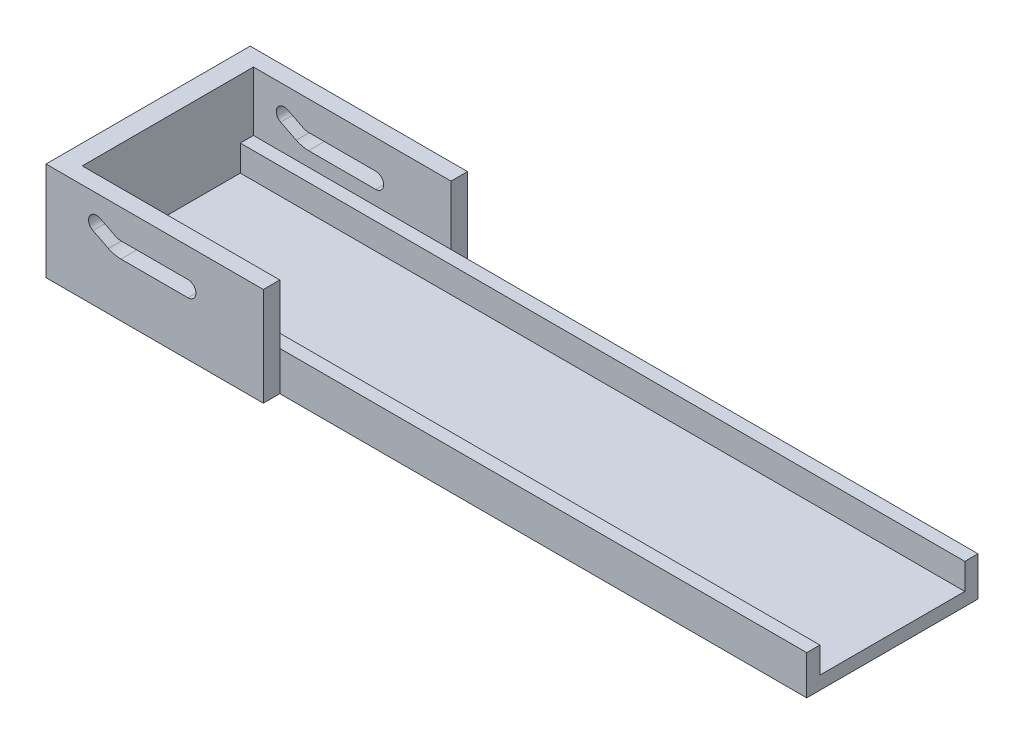
SolidWorks part; units mm, degrees
ref_plane "前视基准面" through (0, 0, 0) normal (0, 0, 1) x (1, 0, 0)
ref_plane "上视基准面" through (0, 0, 0) normal (0, 1, 0) x (1, 0, 0)
ref_plane "右视基准面" through (0, 0, 0) normal (1, 0, 0) x (0, 0, -1)
other "Configuration Table"
sketch "草图1" plane through (0, 0, 0) normal (1, 0, 0) x (0, 0, -1)
  line L0 (-13, 5.95) -> (-13, -5.95)
  line L1 (-11, 3.95) -> (11, 3.95)
  line L2 (-11, 3.95) -> (-11, -3.95)
  line L3 (-11, -3.95) -> (11, -3.95)
  line L4 (11, 3.95) -> (11, -3.95)
  line L5 (-11, 3.95) -> (11, -3.95) construction
  line L6 (-11, -3.95) -> (11, 3.95) construction
  line L7 (-13, -5.95) -> (13, -5.95)
  line L8 (13, 5.95) -> (13, -5.95)
  line L9 (-13, 5.95) -> (13, 5.95)
  line L10 (55, 0) -> (-55, 0) construction
  point P0 (0, 0)
  point P9 (0, 0)
  point P12 (0, 0)
  dimension "D1" = 7.9
  dimension "D2" = 22
  dimension "D3" = 2
extrude "凸台-拉伸1" add sketch "草图1" along normal blind 110
sketch "草图3" plane through (0, 0, 13) normal (0, 0, 1) x (1, 0, 0)
  line L0 (3.6643, 3.3873) -> (3.6643, 5.95)
  line L1 (110, 5.95) -> (0, 5.95) construction
  line L2 (5.6643, 3.3873) -> (5.6643, 5.95)
  line L3 (5.6643, 5.95) -> (3.6643, 5.95)
  line L5 (-3.2135, 0) -> (147.8577, 0)
  line L6 (-3.2135, 0) -> (-3.2135, 8.5216)
  line L7 (-3.2135, 8.5216) -> (147.8577, 8.5216)
  line L8 (147.8577, 0) -> (147.8577, 8.5216)
  arc A0 (3.6643, 3.3873) -> (5.6643, 3.3873) centre (4.6643, 3.3873) ccw
  point P1 (147.8577, 8.5216)
  dimension "D1" = 2
extrude "切除-拉伸1" cut sketch "草图3" against normal blind 50 contours L7 L8 L5 L6
sketch "草图4" plane through (0, 0, 0) normal (-1, 0, 0) x (0, 0, 1)
  line L0 (0, -6.545) -> (0, 6.545) construction
  line L5 (13, 9.0004) -> (15.5, 9.0004)
  line L6 (-13, -5.95) -> (-15.5, -5.95)
  line L7 (15.5, -5.95) -> (15.5, 9.0004)
  line L8 (-13, -5.95) -> (-13, 9.0004)
  line L9 (-13, 9.0004) -> (-15.5, 9.0004)
  line L10 (-15.5, -5.95) -> (-15.5, 9.0004)
  line L11 (13, -5.95) -> (15.5, -5.95)
  line L12 (13, -5.95) -> (13, 9.0004)
  dimension "D1" = 2.5
extrude "凸台-拉伸2" add sketch "草图4" against normal blind 30
sketch "草图5" plane through (0, 0, 0) normal (-1, 0, 0) x (0, 0, 1)
  line L1 (-15.5, 9.0004) -> (15.5, 9.0004)
  line L2 (-15.5, 9.0004) -> (-15.5, -5.95)
  line L3 (-15.5, -5.95) -> (15.5, -5.95)
  line L4 (15.5, 9.0004) -> (15.5, -5.95)
extrude "凸台-拉伸3" add sketch "草图5" along normal blind 3
sketch "草图6" plane through (0, 0, -13) normal (0, 0, 1) x (1, 0, 0)
  line L0 (4.6643, 4.8873) -> (7.6643, 3.3873) construction
  line L1 (5.201, 5.9606) -> (8.201, 4.4606)
  line L2 (4.1276, 3.814) -> (7.1276, 2.314)
  line L3 (7.6643, 3.3873) -> (18.5632, 3.3873) construction
  line L4 (7.6643, 4.5873) -> (18.5632, 4.5873)
  line L5 (7.6643, 2.1873) -> (18.5632, 2.1873)
  arc A0 (5.201, 5.9606) -> (4.1276, 3.814) centre (4.6643, 4.8873) ccw
  arc A1 (7.1276, 2.314) -> (8.201, 4.4606) centre (7.6643, 3.3873) ccw
  arc A3 (7.6643, 4.5873) -> (7.6643, 2.1873) centre (7.6643, 3.3873) ccw
  arc A4 (18.5632, 2.1873) -> (18.5632, 4.5873) centre (18.5632, 3.3873) ccw
  circle A5 centre (8.3795, 6.4168) radius 1.8295
  circle A6 centre (8.3795, 6.4168) radius 4.2295
  point P2 (6.1643, 4.1373)
  point P7 (13.1137, 3.3873)
  point P15 (23.7458, 3.3873)
  point P19 (18.5632, 3.3873)
  dimension "D1" = 1.2
  dimension "D2" = 1.2
  dimension "D3" = 3
  dimension "D4" = 1.5
extrude "切除-拉伸2" cut sketch "草图6" against normal blind 10 and the other way through all contours A6 L5 A4 L4 | A1 A6 L4 L1 | A0 A6 A3 L4 L1 | A5 L1 L4 | A6 A0 L2 | A3 A6 A1 L1 L4
